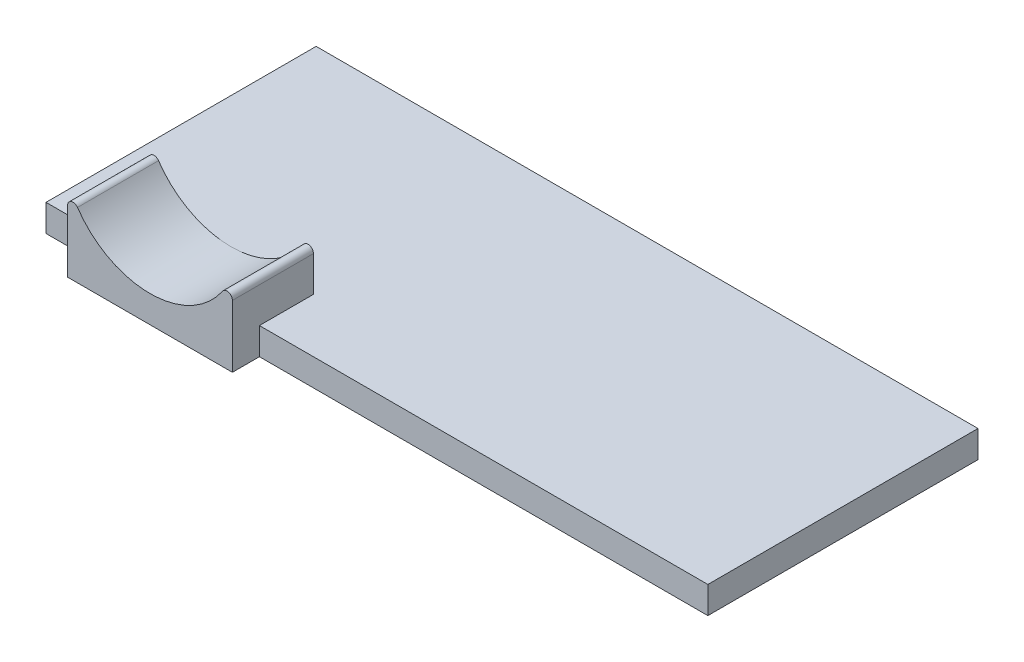
SolidWorks part; units mm, degrees
ref_plane "Front Plane" through (0, 0, 0) normal (0, 0, 1) x (1, 0, 0)
ref_plane "Top Plane" through (0, 0, 0) normal (0, 1, 0) x (1, 0, 0)
ref_plane "Right Plane" through (0, 0, 0) normal (1, 0, 0) x (0, 0, -1)
sketch "Sketch1" plane through (0, 0, 0) normal (0, 1, 0) x (1, 0, 0)
  line L1 (0, 0) -> (-24.5, 0)
  line L2 (0, 0) -> (0, 10)
  line L3 (0, 10) -> (-24.5, 10)
  line L4 (-24.5, 0) -> (-24.5, 10)
  dimension "D1" = 10
  dimension "D2" = 24.5
extrude "Boss-Extrude1" add sketch "Sketch1" along normal blind 1
sketch "Sketch2" plane through (0, 1, 0) normal (0, 1, 0) x (1, 0, 0)
  line L0 (0, 0) -> (-19.65, 0) construction
  line L1 (-24.5, 0) -> (0, 0) construction
  line L2 (-16.6, -1) -> (-22.7, -1)
  line L3 (-22.7, -1) -> (-22.7, 2)
  line L4 (-22.7, 2) -> (-16.6, 2)
  line L5 (-19.65, 2) -> (-19.65, 0) construction
  line L6 (-16.6, -1) -> (-16.6, 2)
  line L7 (-24.5, 10) -> (-24.5, 0) construction
  dimension "D1" = 4.85
  dimension "D2" = 3
  dimension "D3" = 6.1
  dimension "D4" = 1
extrude "Boss-Extrude2" add sketch "Sketch2" along normal blind 3.25
sketch "Sketch4" plane through (0, 1, 0) normal (0, -1, 0) x (-1, 0, 0)
  line L1 (22.7, 0) -> (16.6, 0)
  line L2 (22.7, 0) -> (22.7, -1)
  line L3 (22.7, -1) -> (16.6, -1)
  line L4 (16.6, 0) -> (16.6, -1)
extrude "Boss-Extrude3" add sketch "Sketch4" along normal up to surface (1 mm away) up to face at (-12.25, 0, -5)
sketch "Sketch3" plane through (0, 0, 1) normal (0, 0, 1) x (1, 0, 0)
  line L0 (-22.7, 4.25) -> (-16.6, 4.25) construction
  circle A0 centre (-19.65, 4.25) radius 3.25
  dimension "D1" = 6.5
extrude "Cut-Extrude1" cut sketch "Sketch3" against normal up to surface (3 mm away) up to face at (-19.65, 2.625, -2)
fillet "Fillet1" radius 0.2 2 edges at (-16.6, 3.1275, -0.5) (-22.7, 3.1275, -0.5)
